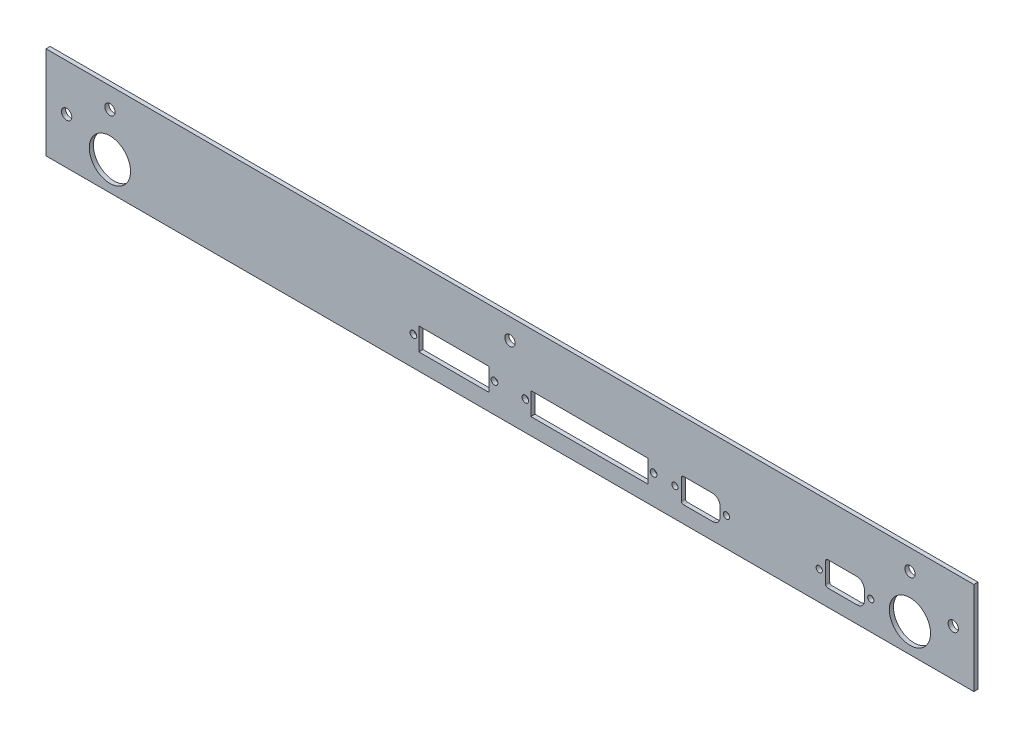
SolidWorks part; units mm, degrees
material "1345 Alloy"
ref_plane "Front Plane" through (0, 0, 0) normal (0, 0, 1) x (1, 0, 0)
ref_plane "Top Plane" through (0, 0, 0) normal (0, 1, 0) x (1, 0, 0)
ref_plane "Right Plane" through (0, 0, 0) normal (1, 0, 0) x (0, 0, -1)
sketch "Sketch1" plane through (0, 0, 0) normal (0, 0, 1) x (1, 0, 0)
  line L1 (-225, 22.5) -> (225, 22.5)
  line L2 (-225, 22.5) -> (-225, -22.5)
  line L3 (-225, -22.5) -> (225, -22.5)
  line L4 (225, 22.5) -> (225, -22.5)
  line L5 (-225, 22.5) -> (225, -22.5) construction
  line L6 (-225, -22.5) -> (225, 22.5) construction
  point P0 (0, 0)
  dimension "D1" = 450
  dimension "D2" = 45
extrude "Boss-Extrude1" add sketch "Sketch1" along normal blind 2
sketch "SK Terminal 12P cutout" plane through (0, 0, 0) normal (0, 0, 1) x (1, 0, 0)
  line L0 (10.125, -14.4) -> (67.045, -14.4)
  line L1 (67.045, -14.4) -> (67.045, -3.5)
  line L2 (67.045, -3.5) -> (10.125, -3.5)
  line L3 (10.125, -3.5) -> (10.125, -14.4)
  line L4 (69.67, 22.5) -> (69.67, -8.35) construction
  line L5 (225, 22.5) -> (-225, 22.5) construction
  line L6 (-7.5, -8.35) -> (-31.415, -8.35) construction
  line L7 (-44.185, -14.4) -> (-10.125, -14.4)
  line L8 (-10.125, -14.4) -> (-10.125, -3.5)
  line L9 (-10.125, -3.5) -> (-44.185, -3.5)
  line L10 (-44.185, -3.5) -> (-44.185, -14.4)
  line L11 (7.5, -8.35) -> (69.67, -8.35) construction
  line L12 (7.5, -8.35) -> (-7.5, -8.35) construction
  line L14 (-31.415, -8.35) -> (-31.415, -3.5) construction
  circle A0 centre (7.5, -8.35) radius 1.625
  circle A1 centre (69.67, -8.35) radius 1.625
  circle A2 centre (-46.81, -8.35) radius 1.625
  circle A3 centre (-7.5, -8.35) radius 1.625
  dimension "D1" = 62.17
  dimension "D2" = 15
extrude "Terminal 12P cutout" cut sketch "SK Terminal 12P cutout" against normal through all and the other way through all
sketch "Sketch2" plane through (0, 0, 2) normal (0, 0, 1) x (1, 0, 0)
  line L0 (-225, 22.5) -> (-215, 22.5) construction
  line L1 (-215, 22.5) -> (-215, 0) construction
  line L2 (-194, 12.4954) -> (194, 12.4954) construction
  line L3 (0, 22.5) -> (0, 12.5) construction
  circle A0 centre (-215, 0) radius 2.5
  circle A1 centre (215, 0) radius 2.5
  circle A2 centre (-194, 12.4954) radius 2.5
  circle A3 centre (194, 12.4954) radius 2.5
  circle A4 centre (0, 12.5) radius 2.5
  dimension "D3" = 5
  dimension "D4" = 5
  dimension "D5" = 5
  dimension "D7" = 5
  dimension "D8" = 5
  dimension "D1" = 10
  dimension "D2" = 22.5
  dimension "D6" = 10
extrude "Cut-Extrude1" cut sketch "Sketch2" against normal through all
sketch "Sketch3" plane through (0, 0, 2) normal (0, 0, 1) x (1, 0, 0)
  line L0 (175, -8.55) -> (225, -8.55) construction
  line L5 (168.375, -14.4) -> (154.1, -14.4)
  line L6 (154.3, -2.5) -> (168.175, -2.5)
  line L7 (153.1, -13.4) -> (153.1, -3.7)
  line L8 (171.9, -10.875) -> (171.9, -6.225)
  line L13 (171.9, -8.55) -> (175, -8.55) construction
  line L14 (194, 12.4954) -> (194, -8.55) construction
  line L15 (225, -22.5) -> (225, 22.5) construction
  line L16 (150, -8.55) -> (153.1, -8.55) construction
  line L17 (98.375, -14.4) -> (84.1, -14.4)
  line L18 (150, -8.55) -> (153.1, -8.55) construction
  line L19 (84.3, -2.5) -> (98.175, -2.5)
  line L20 (83.1, -13.4) -> (83.1, -3.7)
  line L21 (101.9, -10.875) -> (101.9, -6.225)
  line L22 (101.9, -8.55) -> (105, -8.55) construction
  line L23 (80, -8.55) -> (83.1, -8.55) construction
  line L24 (80, -8.55) -> (83.1, -8.55) construction
  line L25 (150, -8.55) -> (105, -8.55) construction
  line L27 (194, -8.55) -> (194, -22.5) construction
  line L28 (-225, -22.5) -> (225, -22.5) construction
  line L29 (194, -22.5) -> (225, -22.5) construction
  line L30 (-194, -8.55) -> (-194, -22.5) construction
  line L31 (-225, -22.5) -> (-194, -22.5) construction
  arc A4 (171.9, -10.875) -> (168.375, -14.4) centre (168.375, -10.875) cw
  arc A5 (171.9, -6.225) -> (168.175, -2.5) centre (168.175, -6.225) ccw
  arc A6 (154.1, -14.4) -> (153.1, -13.4) centre (154.1, -13.4) cw
  arc A7 (153.1, -3.7) -> (154.3, -2.5) centre (154.3, -3.7) cw
  circle A14 centre (150, -8.55) radius 1.5
  circle A15 centre (175, -8.55) radius 1.5
  arc A16 (101.9, -10.875) -> (98.375, -14.4) centre (98.375, -10.875) cw
  arc A17 (101.9, -6.225) -> (98.175, -2.5) centre (98.175, -6.225) ccw
  arc A18 (84.1, -14.4) -> (83.1, -13.4) centre (84.1, -13.4) cw
  arc A19 (83.1, -3.7) -> (84.3, -2.5) centre (84.3, -3.7) cw
  circle A20 centre (80, -8.55) radius 1.5
  circle A21 centre (105, -8.55) radius 1.5
  circle A22 centre (194, -8.55) radius 10
  circle A23 centre (-194, -8.55) radius 10
  dimension "D3" = 3
  dimension "D4" = 3
  dimension "D5" = 3
  dimension "D6" = 3
  dimension "D7" = 25
  dimension "D11" = 20
  dimension "D2" = 50
  dimension "D8" = 5.85
  dimension "D9" = 45
  dimension "D10" = 25
  dimension "D13" = 5.85
extrude "Cut-Extrude2" cut sketch "Sketch3" against normal blind 10
